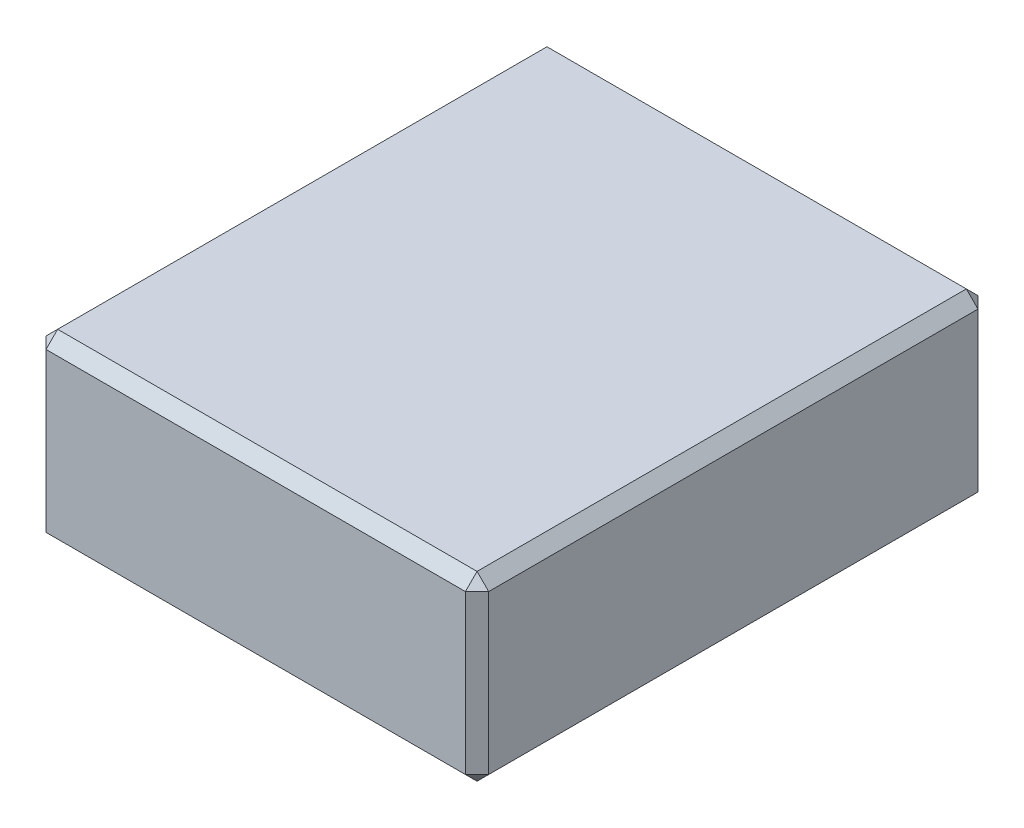
SolidWorks part; units mm, degrees
ref_plane "前视基准面" through (0, 0, 0) normal (0, 0, 1) x (1, 0, 0)
ref_plane "上视基准面" through (0, 0, 0) normal (0, 1, 0) x (1, 0, 0)
ref_plane "右视基准面" through (0, 0, 0) normal (1, 0, 0) x (0, 0, -1)
sketch "草图1" plane through (0, 0, 0) normal (0, 1, 0) x (1, 0, 0)
  line L1 (-95, -110) -> (95, -110)
  line L2 (-95, -110) -> (-95, 110)
  line L3 (-95, 110) -> (95, 110)
  line L4 (95, -110) -> (95, 110)
  line L5 (-95, -110) -> (95, 110) construction
  line L6 (-95, 110) -> (95, -110) construction
  point P0 (0, 0)
  dimension "D1" = 190
  dimension "D2" = 220
extrude "凸台-拉伸1" add sketch "草图1" along normal blind 78
chamfer "倒角1" distance 5 angle 45 12 edges at (-95, 39, -110) (95, 39, -110) (-95, 39, 110) (0, 0, -110) (-95, 0, 0) (0, 0, 110) (95, 0, 0) (95, 39, 110) (0, 78, 110) (-95, 78, 0) (0, 78, -110) (95, 78, 0)
